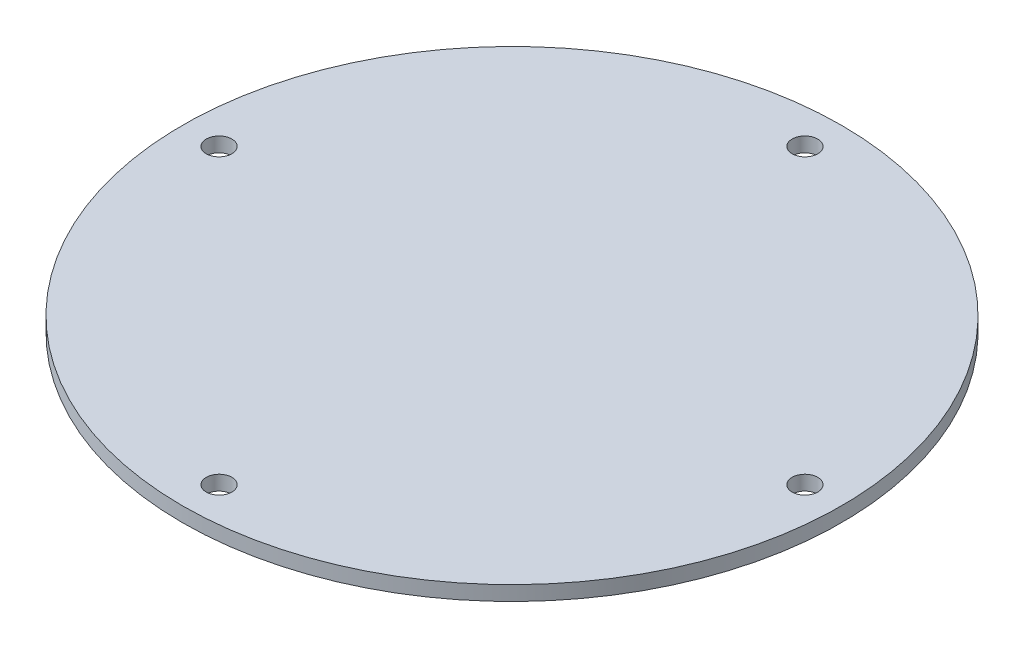
SolidWorks part; units mm, degrees
ref_plane "Front Plane" through (0, 0, 0) normal (0, 0, 1) x (1, 0, 0)
ref_plane "Top Plane" through (0, 0, 0) normal (0, 1, 0) x (1, 0, 0)
ref_plane "Right Plane" through (0, 0, 0) normal (1, 0, 0) x (0, 0, -1)
sketch "Sketch2" plane through (0, 0, 0) normal (0, 1, 0) x (1, 0, 0)
  circle A0 centre (0, 0) radius 45
  dimension "D1" = 90
extrude "Boss-Extrude1" add sketch "Sketch2" along normal blind 2
sketch "Sketch4" plane through (0, 2, 0) normal (0, 1, 0) x (1, 0, 0)
  circle A0 centre (0, 40) radius 1.75
  circle A1 centre (40, 0) radius 1.75
  circle A2 centre (0, -40) radius 1.75
  circle A3 centre (-40, 0) radius 1.75
  circle A4 centre (0, 0) radius 45 construction
  point P0 (0, 0)
  point P1 (0, 40)
  point P14 (0, 0)
  dimension "D2" = 3.5
  dimension "D1" = 40
  dimension "D3" = 4
extrude "Cut-Extrude1" cut sketch "Sketch4" against normal through all
